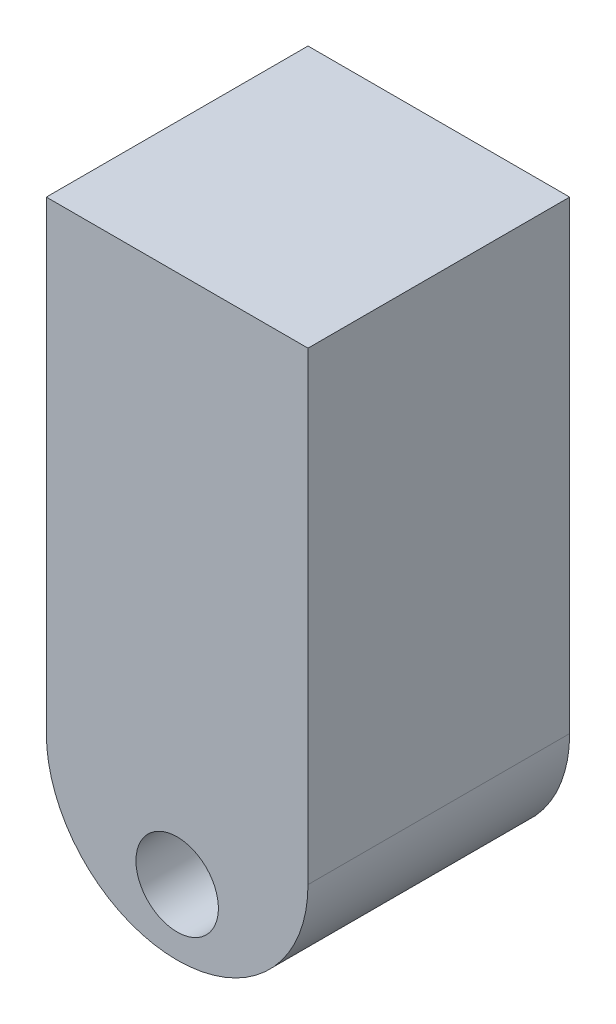
SolidWorks part; units mm, degrees
ref_plane "Front Plane" through (0, 0, 0) normal (0, 0, 1) x (1, 0, 0)
ref_plane "Top Plane" through (0, 0, 0) normal (0, 1, 0) x (1, 0, 0)
ref_plane "Right Plane" through (0, 0, 0) normal (1, 0, 0) x (0, 0, -1)
sketch "Sketch1" plane through (0, 0, 0) normal (0, 0, 1) x (1, 0, 0)
  line L0 (-13.9623, 14.9955) -> (5.0877, 14.9955)
  line L1 (-13.9623, 14.9955) -> (-13.9623, 6.5708)
  line L2 (5.0877, 14.9955) -> (5.0877, 6.5708)
  arc A0 (-13.9623, 6.5708) -> (5.0877, 6.5708) centre (-4.4373, 6.5708) ccw
  circle A3 centre (-4.4373, 1.8201) radius 3
  dimension "D1" = 19.05
extrude "Boss-Extrude1" add sketch "Sketch1" along normal blind 19.05
sketch "Sketch3" plane through (0, 14.9955, 0) normal (0, 1, 0) x (1, 0, 0)
  line L0 (5.0877, -19.05) -> (-13.9623, -19.05) construction
  line L1 (-13.9623, 0) -> (5.0877, 0)
  line L2 (-13.9623, 0) -> (-13.9623, -19.05)
  line L3 (-13.9623, -19.05) -> (5.0877, -19.05)
  line L4 (5.0877, 0) -> (5.0877, -19.05)
extrude "Boss-Extrude2" add sketch "Sketch3" along normal blind 25.4
